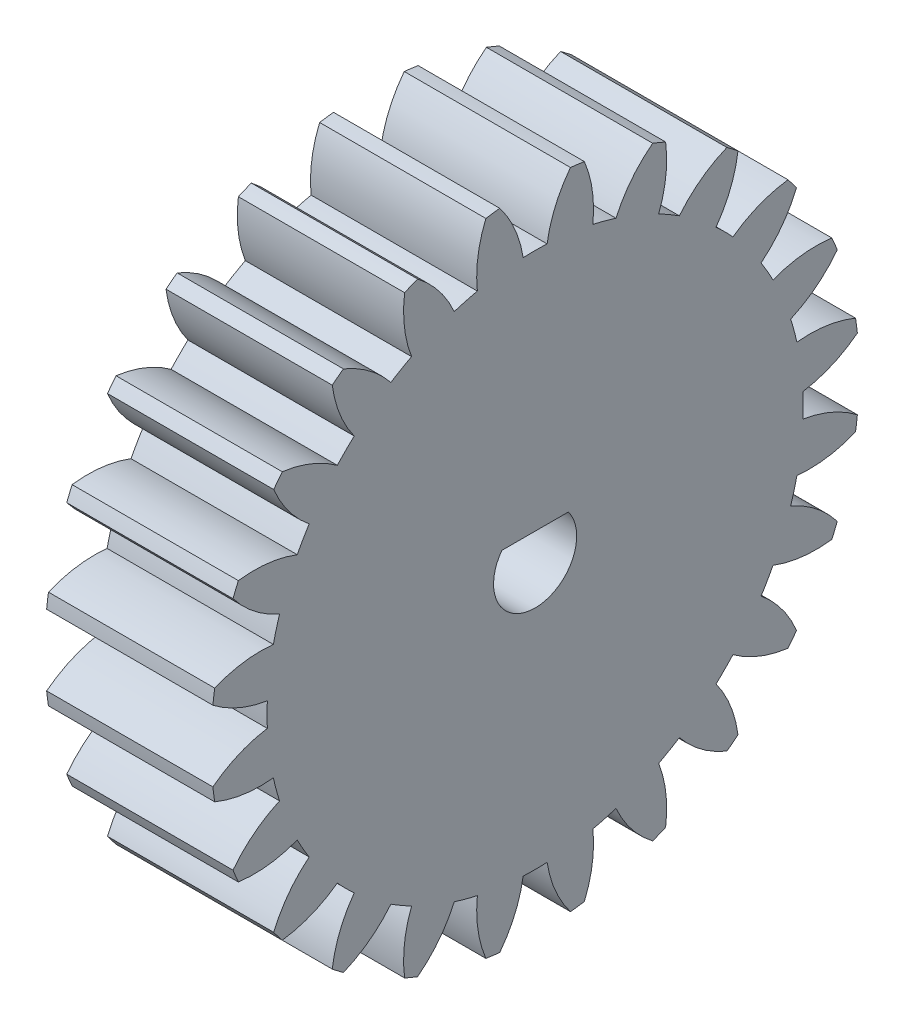
SolidWorks part; units mm, degrees
ref_plane "Plane1" through (0, 0, 0) normal (0, 0, 1) x (1, 0, 0)
ref_plane "Plane2" through (0, 0, 0) normal (0, 1, 0) x (1, 0, 0)
ref_plane "Plane3" through (0, 0, 0) normal (1, 0, 0) x (0, 0, -1)
sketch "HoldingSke" plane through (0, 0, 0) normal (0, 1, 0) x (1, 0, 0)
  line L0 (0, 0) -> (0.609, -0.2712)
  line L1 (-15, 0) -> (100, 0) construction
  line L2 (0, 0) -> (-2.1039, 2.3779)
  line L3 (0, 0) -> (-11.863, 4.5341)
  line L4 (0, 0) -> (7.8894, 3.5126)
  line L5 (0, 0) -> (-46.8476, -17.4728)
  line L6 (0, 0) -> (-8.2896, -5.593)
  line L7 (-2.1039, 2.3779) -> (8.6586, 51.2059)
  line L8 (-76.2, 54.61) -> (-75.3, 54.61)
  line L9 (-71.009, 38.7566) -> (-53.1078, 45.2721)
  line L10 (-76.2, 71.12) -> (104.1128, 71.12)
  line L11 (0, 0) -> (-10, 0)
  line L12 (-76.2, 101.6) -> (-76.147, 101.6)
  line L13 (24.9733, 27.94) -> (52.9518, 28.4284)
  line L14 (24.9733, 27.94) -> (24.9743, 27.94)
  line L15 (24.9733, 27.94) -> (100.4006, 29.5858)
  line L16 (-63.627, -1.5) -> (-12.827, -1.5)
  circle A0 centre (0, 0) radius 2.5
  circle A1 centre (0, 0) radius 16.124
  circle A2 centre (0, 0) radius 37.5
  circle A3 centre (0, 0) radius 2.5
  dimension "MHD" = 32.248
  dimension "Hub_dia" = 75
  dimension "Bore" = 5
  dimension "MBD" = 5
  dimension "Num_teeth" = 24
  dimension "Pitch" = 0.6667
  dimension "Overall_len" = 50
  dimension "Show_teeth" = 24
  dimension "Thickness" = 10
  dimension "OAL" = 50.0001
  dimension "T_dim" = 0.9
  dimension "Ap" = 20
  dimension "H" = 19.05
  dimension "Pitch_radius" = 180.3128
  dimension "Width" = 10
  dimension "Backlash" = 0.053
  dimension "Addendum_fac" = 1
  dimension "Dedendum_fac" = 1.25
  dimension "Clearance_fac" = 0.25
  dimension "Dedendum_add" = 0.001
  dimension "Module" = 1.5
sketch "BasProSke" plane through (0, 0, 0) normal (0, 1, 0) x (1, 0, 0)
  line L0 (-10, 0) -> (60, 0) construction
  line L1 (0, 0) -> (0, 19.5)
  line L2 (0, 0) -> (10, 0)
  line L3 (10, 0) -> (10, 19.5)
  line L4 (10, 19.5) -> (0, 19.5)
  dimension "Thickness" = 10
  dimension "Diameter" = 39
revolve "Base-Revolve" add sketch "BasProSke" angle 360 about L0
sketch "TooCutSke" plane through (0, 0, 0) normal (1, 0, 0) x (0, 0, -1)
  line L1 (0, 0) -> (0, 107) construction
  line L2 (0, 0) -> (-1.27, 17.9551) construction
  line L3 (0, 0) -> (-4.6904, 35.6272) construction
  line L4 (-1.27, 17.9551) -> (-2.3452, 17.8136) construction
  arc A0 (0.719, 16.108) -> (-0.719, 16.108) centre (0, 0) ccw
  arc A1 (2.1447, 19.4073) -> (-2.1447, 19.4073) centre (0, 0) ccw
  circle A2 centre (0, 0) radius 18 construction
  circle A3 centre (0, 0) radius 16.9145 construction
  arc A4 (-0.719, 16.108) -> (-2.1447, 19.4073) centre (-7.832, 14.992) ccw
  arc A5 (2.1447, 19.4073) -> (0.719, 16.108) centre (7.832, 14.992) ccw
  dimension "Root_dia" = 32.248
  dimension "Overcut_dia" = 39.0508
  dimension "Pitch_dia" = 36
  dimension "Base_dia" = 33.8289
  dimension "Flank_rad" = 7.2
  dimension "Half_ang" = 7.5
  dimension "Half_CT" = 1.0845
extrude "ToothCut" cut sketch "TooCutSke" along normal through all
fillet "Breaks" [suppressed] radius 0.03
fillet "RootFillets" [suppressed] radius 0.376
pattern_circular "TeethCuts" count 24 every 15 about axis through (-10, 0, 0) along (1, 0, 0) of "ToothCut", "RootFillets", "Breaks"
sketch "HubNeaOneSke" plane through (0, 0, 0) normal (-1, 0, 0) x (0, 0, 1)
  circle A0 centre (0, 0) radius 16.124
  dimension "Diameter" = 32.248
extrude "HubNearOne" [suppressed] add sketch "HubNeaOneSke" along normal blind 40.0001
sketch "HubNeaBotSke" plane through (0, 0, 0) normal (-1, 0, 0) x (0, 0, 1)
  circle A0 centre (0, 0) radius 16.124
  dimension "Diameter" = 32.248
extrude "HubNearBoth" [suppressed] add sketch "HubNeaBotSke" along normal blind 20
ref_plane "FarPln" through (10, 0, 0) normal (1, 0, 0) x (0, 0, -1)
sketch "HubFarSke" plane through (10, 0, 0) normal (1, 0, 0) x (0, 0, -1)
  circle A0 centre (0, 0) radius 16.124
  dimension "Diameter" = 32.248
extrude "HubFar" [suppressed] add sketch "HubFarSke" along normal blind 20
sketch "BorSke" plane through (0, 0, 0) normal (1, 0, 0) x (0, 0, -1)
  circle A0 centre (0, 0) radius 2.5
  dimension "Diameter" = 5
extrude "Bore" cut sketch "BorSke" along normal mid plane 100.0001
sketch "KeySke" plane through (0, 0, 0) normal (1, 0, 0) x (0, 0, -1)
  line L0 (-1, 0) -> (-1, 3.4)
  line L1 (-1, 3.4) -> (1, 3.4)
  line L2 (1, 3.4) -> (1, 0)
  line L3 (0, 0) -> (0, 34) construction
  line L4 (-1, 0) -> (1, 0)
  dimension "Offset" = 3.4
  dimension "Width" = 2
extrude "Keyway" [suppressed] cut sketch "KeySke" along normal mid plane 100.0001
pattern_circular "Keyway2" [suppressed] count 2 every 90 about axis through (-10, 0, 0) along (1, 0, 0)
sketch "Sketch1" plane through (10, 0, 0) normal (1, 0, 0) x (0, 0, -1)
  line L0 (2, 1.5) -> (-2, 1.5)
  circle A0 centre (0, 0) radius 2.5
  dimension "D2" = 5
  dimension "D1" = 1.5
extrude "Boss-Extrude1" add sketch "Sketch1" against normal blind 10 contours L0 A0
equation "' \"Module@HoldingSke\" = 6.35"
equation "' \"Num_teeth@HoldingSke\" = 12"
equation "' \"Ap@HoldingSke\" =  20"
equation "' \"Ap@HoldingSke\" = 20"
equation "' \"Width@HoldingSke\" = 0.5 * 25.4"
equation "' \"Hub_dia@HoldingSke\"= 1 * 25.4"
equation "' \"Hub_dia@HoldingSke\" = 1 * 25.4"
equation "' \"Overall_len@HoldingSke\" = 1.0 * 25.4"
equation "' \"Bore@HoldingSke\" = 0.75 * 25.4"
equation "' \"T_dim@HoldingSke\" = 0.1 * 25.4"
equation "' \"Width@KeySke\" = 0.25 * 25.4"
equation "' \"Show_teeth@HoldingSke\" = 13"
equation "' \"Backlash@HoldingSke\" = 0.009 * 25.4"
equation "' \"Addendum_fac@HoldingSke\" = 1.0"
equation "' \"Dedendum_fac@HoldingSke\" = 1.25"
equation "' \"Dedendum_add@HoldingSke\" = 0.00005 * 25.4"
equation "' \"Clearance_fac@HoldingSke\" = 0.25"
equation "\"Pitch@HoldingSke\" = 1 / \"Module@HoldingSke\""
equation "\"Overcut_dia@TooCutSke\" = (\"Num_teeth@HoldingSke\" + 2 * \"Addendum_fac@HoldingSke\") / \"Pitch@HoldingSke\" + 0.002 * 25.4"
equation "\"Pitch_dia@TooCutSke\" = \"Num_teeth@HoldingSke\" / \"Pitch@HoldingSke\""
equation "\"Base_dia@TooCutSke\" = \"Num_teeth@HoldingSke\" / \"Pitch@HoldingSke\" * cos((\"Ap@HoldingSke\"  * 3.14159265 / 180))"
equation "\"Root_dia@TooCutSke\" = (\"Num_teeth@HoldingSke\" + 2) / \"Pitch@HoldingSke\" - 2 * (\"Addendum_fac@HoldingSke\" + \"Dedendum_fac@HoldingSke\") / \"Pitch@HoldingSke\" - \"Dedendum_add@HoldingSke\" * 2"
equation "\"Half_ang@TooCutSke\" = 180 / \"Num_teeth@HoldingSke\""
equation "\"Half_CT@TooCutSke\" = \"Num_teeth@HoldingSke\" / \"Pitch@HoldingSke\" * sin((3.14159265 / 2 / \"Num_teeth@HoldingSke\")) / 2 - 7 * \"Backlash@HoldingSke\" / 4"
equation "\"Flank_rad@TooCutSke\" = \"Num_teeth@HoldingSke\" / \"Pitch@HoldingSke\" / 5"
equation "\"Radius@RootFillets\" = \"Clearance_fac@HoldingSke\" / \"Pitch@HoldingSke\" + \"Dedendum_add@HoldingSke\""
equation "\"Break_rad@Breaks\" = 0.02 / \"Pitch@HoldingSke\""
equation "\"Thickness@HoldingSke\" = \"Width@HoldingSke\""
equation "\"OAL@HoldingSke\" = \"Thickness@HoldingSke\""
equation "\"MHD@HoldingSke\" = (\"Num_teeth@HoldingSke\" + 2) / \"Pitch@HoldingSke\" - 2 * (\"Addendum_fac@HoldingSke\" + \"Dedendum_fac@HoldingSke\")  / \"Pitch@HoldingSke\" - \"Dedendum_add@HoldingSke\" * 2"
equation "\"MBD@HoldingSke\" = (\"Num_teeth@HoldingSke\" + 2) / \"Pitch@HoldingSke\" - 2 * (\"Addendum_fac@HoldingSke\" + \"Dedendum_fac@HoldingSke\")  / \"Pitch@HoldingSke\" - \"Dedendum_add@HoldingSke\" * 2 - 0.002 * 25.4"
equation "\"MHD@HoldingSke\" = ((sgn( \"MHD@HoldingSke\" - \"Hub_dia@HoldingSke\" )-1)*( \"MHD@HoldingSke\" - \"Hub_dia@HoldingSke\" ))/-2+ \"Hub_dia@HoldingSke\""
equation "\"MBD@HoldingSke\" = ((sgn( \"MBD@HoldingSke\" - \"Bore@HoldingSke\" )-1)*( \"MBD@HoldingSke\" - \"Bore@HoldingSke\" ))/-2+ \"Bore@HoldingSke\""
equation "\"OAL@HoldingSke\" = ((sgn( \"OAL@HoldingSke\" - \"Overall_len@HoldingSke\" )+1)*( \"OAL@HoldingSke\" - \"Overall_len@HoldingSke\" ))/2 + \"Overall_len@HoldingSke\" + 0.000002 * 25.4"
equation "\"Num_teeth@TeethCuts\" = int( \"Show_teeth@HoldingSke\" ) + 1"
equation "\"Num_teeth@TeethCuts\" = ((sgn( \"Num_teeth@TeethCuts\" - \"Num_teeth@HoldingSke\" )-1)*( \"Num_teeth@TeethCuts\" - \"Num_teeth@HoldingSke\" ))/-2+ \"Num_teeth@HoldingSke\""
equation "\"Num_teeth@TeethCuts\" = ((sgn( \"Num_teeth@TeethCuts\" - 2.0)+1)*( \"Num_teeth@TeethCuts\" - 2.0))/2 +2.0"
equation "\"Angle@TeethCuts\" = 360.0 / \"Num_teeth@HoldingSke\""
equation "\"Diameter@BasProSke\" = (\"Num_teeth@HoldingSke\" + 2 * \"Addendum_fac@HoldingSke\") / \"Pitch@HoldingSke\""
equation "\"Thickness@BasProSke\"  = \"Thickness@HoldingSke\""
equation "' \"Fillet_rad@BasProSke\" =  \"Thickness@HoldingSke\" * 0.05"
equation "' \"Fillet_rad@BasProSke\" = \"Thickness@HoldingSke\" * 0.05"
equation "\"MHD@HoldingSke\" = ((sgn( \"MHD@HoldingSke\" - \"Root_dia@TooCutSke\" )-1)*( \"MHD@HoldingSke\" - \"Root_dia@TooCutSke\" ))/-2+ \"Root_dia@TooCutSke\""
equation "\"Diameter@HubNeaOneSke\" = \"MHD@HoldingSke\""
equation "\"Length@HubNearOne\" = \"OAL@HoldingSke\" - \"Thickness@BasProSke\""
equation "\"Diameter@HubNeaBotSke\" = \"MHD@HoldingSke\""
equation "\"Length@HubNearBoth\" = ( \"OAL@HoldingSke\" - \"Thickness@BasProSke\" ) / 2.0"
equation "\"Thickness@FarPln\" = \"Thickness@BasProSke\""
equation "\"Diameter@HubFarSke\" = \"MHD@HoldingSke\""
equation "\"Length@HubFar\" = ( \"OAL@HoldingSke\" - \"Thickness@BasProSke\" ) / 2.0"
equation "\"Diameter@BorSke\" = \"MBD@HoldingSke\""
equation "\"D1@Bore\" = \"OAL@HoldingSke\" * 2.0"
equation "\"D1@Keyway\" = \"OAL@HoldingSke\" * 2.0"
equation "\"Offset@KeySke\" = \"T_dim@HoldingSke\" + \"MBD@HoldingSke\" / 2.0"
